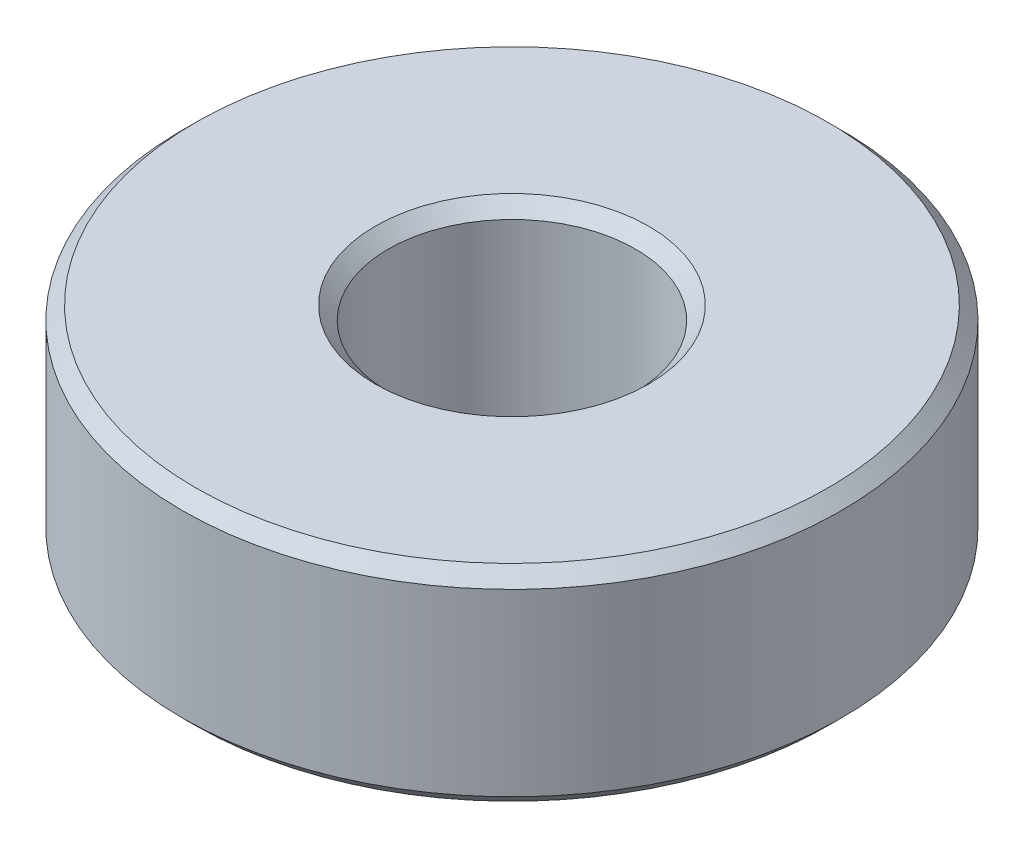
SolidWorks part; units mm, degrees
ref_plane "Front Plane" through (0, 0, 0) normal (0, 0, 1) x (1, 0, 0)
ref_plane "Top Plane" through (0, 0, 0) normal (0, 1, 0) x (1, 0, 0)
ref_plane "Right Plane" through (0, 0, 0) normal (1, 0, 0) x (0, 0, -1)
sketch "Sketch1" plane through (0, 0, 0) normal (0, 1, 0) x (1, 0, 0)
  circle A0 centre (0, 0) radius 6.35
  dimension "D1" = 12.7
extrude "Boss-Extrude1" add sketch "Sketch1" along normal blind 3.9688
hole_wizard "3/16 (0.1875) Diameter Hole1" positions "Sketch2" profile "Sketch3" hole size "3/16" standard "ANSI Inch" end condition through all
sketch "Sketch2" plane through (0, 3.9688, 0) normal (0, 1, 0) x (1, 0, 0)
  point P0 (0, 0)
sketch "Sketch3" plane through (0, 3.9688, 0) normal (1, 0, 0) x (0, 0, 1)
  line L0 (0, 0) -> (0, 3.9688)
  line L1 (0, 3.9688) -> (2.3812, 3.9688)
  line L2 (2.3812, 3.9688) -> (2.3812, 0)
  line L5 (2.3812, 0) -> (0, 0)
  line L11 (0, -6.35) -> (0, 107.95) construction
  dimension "Thru Hole Dia." = 4.7625
  dimension "Thru Hole Depth" = 3.9688
chamfer "Chamfer1" distance 0.254 angle 45 4 edges at (0, 0, 6.35) (0, 3.9688, 6.35) (0, 3.9688, 2.3812) (0, 0, 2.3812)
